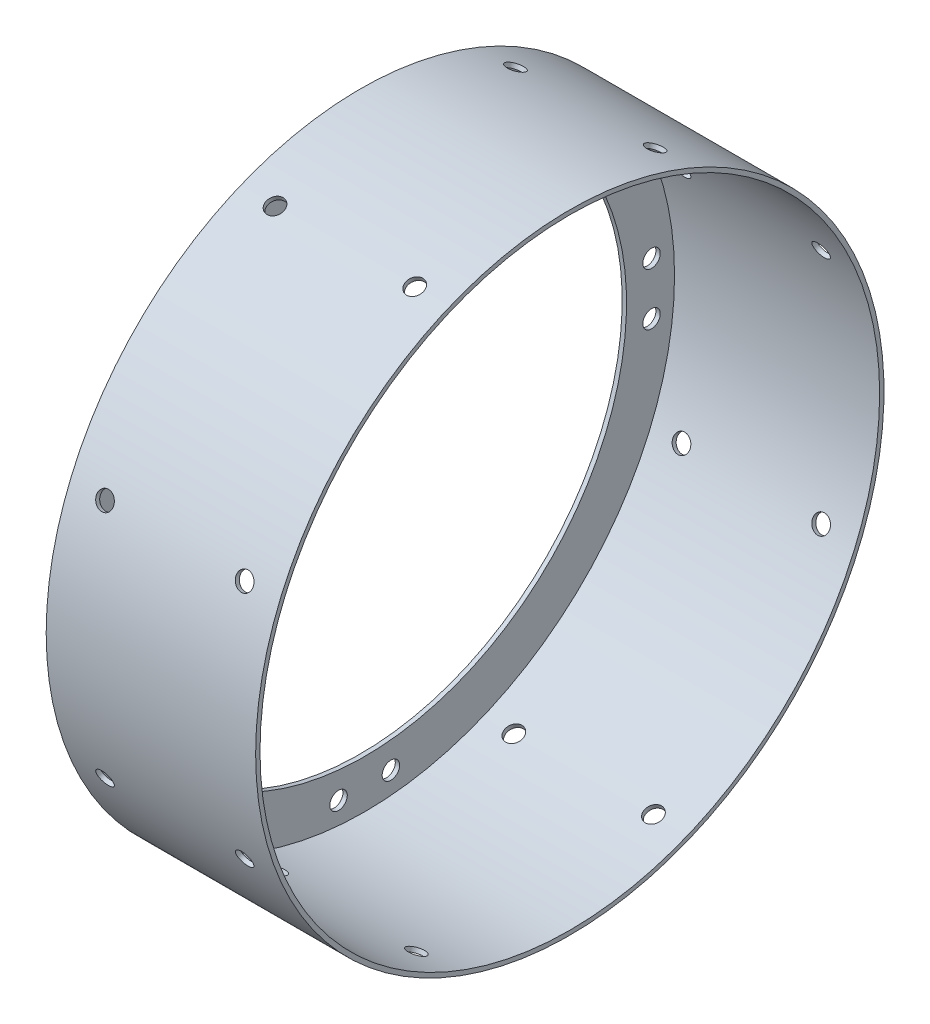
SolidWorks part; units mm, degrees
ref_plane "Front Plane" through (0, 0, 0) normal (0, 0, 1) x (1, 0, 0)
ref_plane "Top Plane" through (0, 0, 0) normal (0, 1, 0) x (1, 0, 0)
ref_plane "Right Plane" through (0, 0, 0) normal (1, 0, 0) x (0, 0, -1)
sketch "Sketch3" plane through (0, 0, 0) normal (0, 1, 0) x (1, 0, 0)
  line L0 (0, 114.3) -> (76.2, 114.3)
  line L1 (76.2, 114.3) -> (76.2, 112.7125)
  line L2 (76.2, 112.7125) -> (1.5875, 112.7125)
  line L3 (1.5875, 112.7125) -> (1.5875, 95.25)
  line L4 (1.5875, 95.25) -> (0, 95.25)
  line L5 (0, 95.25) -> (0, 114.3)
  line L6 (0, 0) -> (369.543, 0) construction
  dimension "D1" = 228.6
  dimension "D2" = 19.05
  dimension "D3" = 1.5875
  dimension "D4" = 1.5875
  dimension "D5" = 76.2
revolve "Revolve1" add sketch "Sketch3" angle 360 about L6
ref_plane "Plane1" through (0, 105.5994, -43.7407) normal (0, 0.9239, -0.3827) x (-1, 0, 0)
sketch "Sketch4" plane through (0, 0, 0) normal (-1, 0, 0) x (0, 0, 1)
  line L0 (0, 0) -> (0, 114.3) construction
  circle A0 centre (0, 0) radius 104.775 construction
  circle A1 centre (0, 0) radius 114.3 construction
  circle A2 centre (9.525, 104.3411) radius 3.175
  circle A3 centre (-9.525, 104.3411) radius 3.175
  circle A8 centre (104.3411, -9.525) radius 3.175
  circle A9 centre (104.3411, 9.525) radius 3.175
  circle A10 centre (-9.525, -104.3411) radius 3.175
  circle A11 centre (9.525, -104.3411) radius 3.175
  circle A12 centre (-104.3411, 9.525) radius 3.175
  circle A13 centre (-104.3411, -9.525) radius 3.175
  point P25 (0, 0)
  dimension "D1" = 209.55
  dimension "D3" = 6.35
  dimension "D2" = 19.05
  dimension "D4" = 4
extrude "Cut-Extrude1" cut sketch "Sketch4" against normal through all
sketch "Sketch5" plane through (0, 76.3728, -114.3) normal (0, -0.9239, 0.3827) x (1, 0, 0)
  line L0 (0, 76.3728) -> (76.2, 76.3728) construction
  line L1 (76.2, -37.9272) -> (76.2, 190.6728) construction
  line L2 (38.1, 76.3728) -> (38.1, 51.0024) construction
  circle A0 centre (12.7, 76.3728) radius 3.175
  circle A1 centre (63.5, 76.3728) radius 3.175
  dimension "D2" = 6.35
  dimension "D3" = 12.7
extrude "Cut-Extrude2" cut sketch "Sketch5" along normal blind 2.54
pattern_circular "CirPattern1" count 8 over 360 about axis through (76.2, 0, 0) along (-1, 0, 0) of "Cut-Extrude2"
